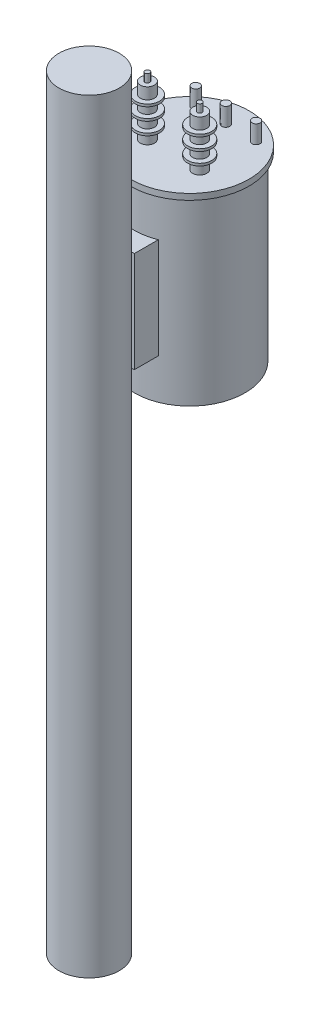
SolidWorks part; units mm, degrees
ref_plane "Front Plane" through (0, 0, 0) normal (0, 0, 1) x (1, 0, 0)
ref_plane "Top Plane" through (0, 0, 0) normal (0, 1, 0) x (1, 0, 0)
ref_plane "Right Plane" through (0, 0, 0) normal (1, 0, 0) x (0, 0, -1)
sketch "Sketch1" plane through (0, 0, 0) normal (0, 1, 0) x (1, 0, 0)
  circle A0 centre (0, 0) radius 275
extrude "Tank" add sketch "Sketch1" along normal blind 900 separate body
sketch "Sketch2" plane through (0, 0, 0) normal (0, 1, 0) x (1, 0, 0)
  circle A0 centre (0, 0) radius 295
extrude "Lid" add sketch "Sketch2" along normal blind 30 from offset 900 separate body
sketch "Sketch3" plane through (0, 0, 0) normal (0, 1, 0) x (1, 0, 0)
  circle A0 centre (0, -500) radius 150
extrude "Pole" add sketch "Sketch3" along normal blind 3800 from offset 2300 separate body
sketch "Sketch4" plane through (0, 0, 0) normal (0, 1, 0) x (1, 0, 0)
  circle A0 centre (-130, -80) radius 35
extrude "Bushing HV 1" add sketch "Sketch4" along normal blind 250 from offset 930 separate body
sketch "Sketch5" plane through (0, 0, 0) normal (0, 1, 0) x (1, 0, 0)
  circle A0 centre (-130, -80) radius 60
extrude "Shed HV 1 1" add sketch "Sketch5" along normal blind 12 from offset 986.5 separate body
sketch "Sketch6" plane through (0, 0, 0) normal (0, 1, 0) x (1, 0, 0)
  circle A0 centre (-130, -80) radius 60
extrude "Shed HV 1 2" add sketch "Sketch6" along normal blind 12 from offset 1049 separate body
sketch "Sketch7" plane through (0, 0, 0) normal (0, 1, 0) x (1, 0, 0)
  circle A0 centre (-130, -80) radius 60
extrude "Shed HV 1 3" add sketch "Sketch7" along normal blind 12 from offset 1111.5 separate body
sketch "Sketch8" plane through (0, 0, 0) normal (0, 1, 0) x (1, 0, 0)
  circle A0 centre (-130, -80) radius 12
extrude "Terminal HV 1" add sketch "Sketch8" along normal blind 40 from offset 1180 separate body
sketch "Sketch9" plane through (0, 0, 0) normal (0, 1, 0) x (1, 0, 0)
  circle A0 centre (130, -80) radius 35
extrude "Bushing HV 2" add sketch "Sketch9" along normal blind 250 from offset 930 separate body
sketch "Sketch10" plane through (0, 0, 0) normal (0, 1, 0) x (1, 0, 0)
  circle A0 centre (130, -80) radius 60
extrude "Shed HV 2 1" add sketch "Sketch10" along normal blind 12 from offset 986.5 separate body
sketch "Sketch11" plane through (0, 0, 0) normal (0, 1, 0) x (1, 0, 0)
  circle A0 centre (130, -80) radius 60
extrude "Shed HV 2 2" add sketch "Sketch11" along normal blind 12 from offset 1049 separate body
sketch "Sketch12" plane through (0, 0, 0) normal (0, 1, 0) x (1, 0, 0)
  circle A0 centre (130, -80) radius 60
extrude "Shed HV 2 3" add sketch "Sketch12" along normal blind 12 from offset 1111.5 separate body
sketch "Sketch13" plane through (0, 0, 0) normal (0, 1, 0) x (1, 0, 0)
  circle A0 centre (130, -80) radius 12
extrude "Terminal HV 2" add sketch "Sketch13" along normal blind 40 from offset 1180 separate body
sketch "Sketch14" plane through (0, 0, 0) normal (0, 1, 0) x (1, 0, 0)
  circle A0 centre (-150, 180) radius 20
extrude "LV bushing 1" add sketch "Sketch14" along normal blind 90 from offset 930 separate body
sketch "Sketch15" plane through (0, 0, 0) normal (0, 1, 0) x (1, 0, 0)
  circle A0 centre (0, 180) radius 20
extrude "LV bushing 2" add sketch "Sketch15" along normal blind 90 from offset 930 separate body
sketch "Sketch16" plane through (0, 0, 0) normal (0, 1, 0) x (1, 0, 0)
  circle A0 centre (150, 180) radius 20
extrude "LV bushing 3" add sketch "Sketch16" along normal blind 90 from offset 930 separate body
sketch "Sketch17" plane through (0, 0, 0) normal (0, 1, 0) x (1, 0, 0)
  line L1 (-100, -375) -> (100, -375)
  line L2 (-100, -375) -> (-100, -250)
  line L3 (-100, -250) -> (100, -250)
  line L4 (100, -375) -> (100, -250)
  line L5 (-100, -375) -> (100, -250) construction
  line L6 (-100, -250) -> (100, -375) construction
  point P0 (0, -312.5)
extrude "Hanger" add sketch "Sketch17" along normal blind 500 from offset 200 separate body
